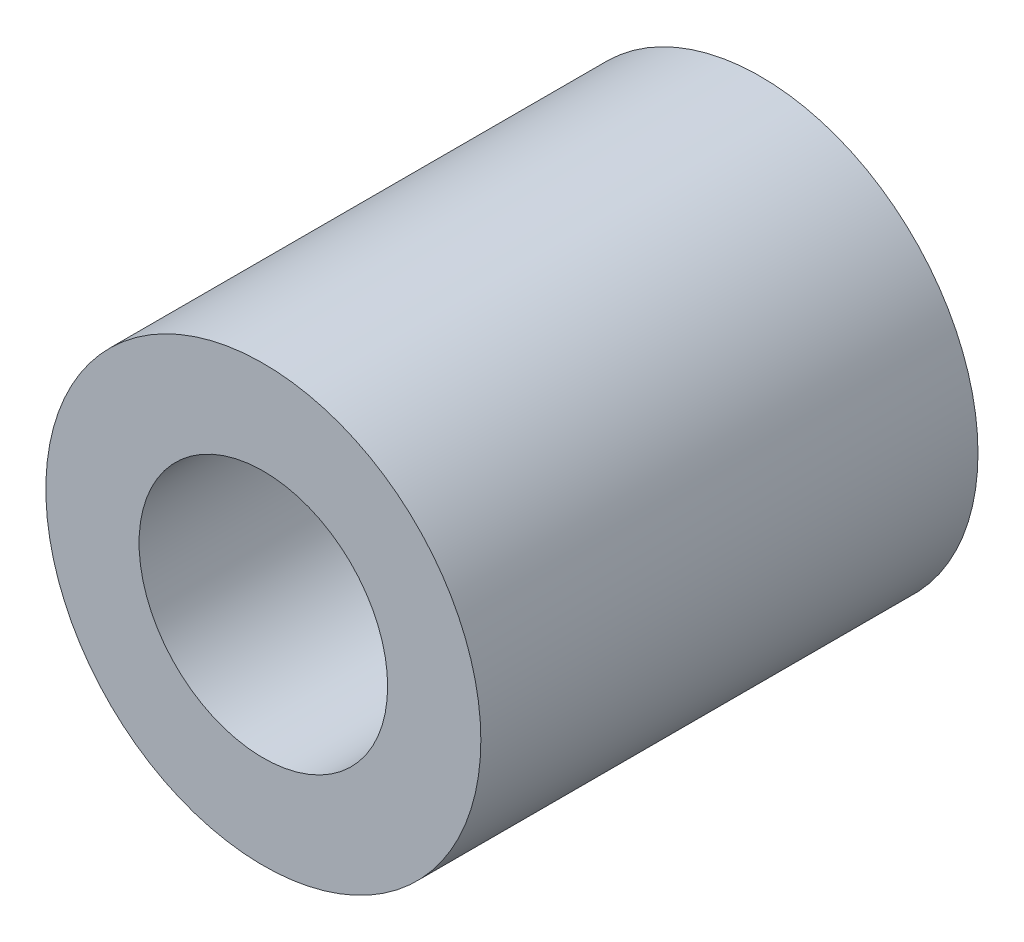
SolidWorks part; units mm, degrees
ref_plane "Front Plane" through (0, 0, 0) normal (0, 0, 1) x (1, 0, 0)
ref_plane "Top Plane" through (0, 0, 0) normal (0, 1, 0) x (1, 0, 0)
ref_plane "Right Plane" through (0, 0, 0) normal (1, 0, 0) x (0, 0, -1)
sketch "Sketch1" plane through (0, 0, 0) normal (0, 0, 1) x (1, 0, 0)
  circle A0 centre (0, 0) radius 6.35
  circle A1 centre (0, 0) radius 11.1125
  dimension "D1" = 12.7
  dimension "D2" = 22.225
extrude "Boss-Extrude1" add sketch "Sketch1" along normal mid plane 25.4
